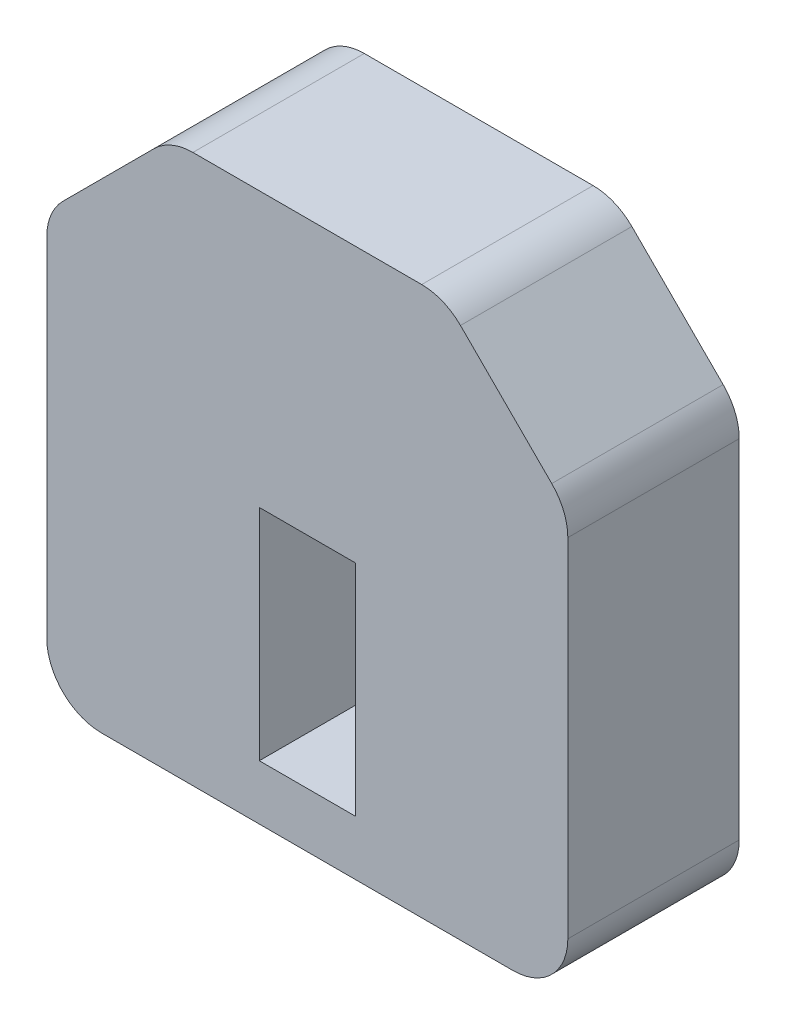
SolidWorks part; units mm, degrees
ref_plane "Front Plane" through (0, 0, 0) normal (0, 0, 1) x (1, 0, 0)
ref_plane "Top Plane" through (0, 0, 0) normal (0, 1, 0) x (1, 0, 0)
ref_plane "Right Plane" through (0, 0, 0) normal (1, 0, 0) x (0, 0, -1)
sketch "Sketch1" plane through (0, 0, 0) normal (0, 0, 1) x (1, 0, 0)
  line L1 (19, -20) -> (-19, -20)
  line L2 (19, -20) -> (19, 20)
  line L3 (19, 20) -> (-19, 20)
  line L4 (-19, -20) -> (-19, 20)
  line L5 (19, -20) -> (-19, 20) construction
  line L6 (19, 20) -> (-19, -20) construction
  point P0 (0, 0)
  dimension "D1" = 38
  dimension "D2" = 40
extrude "Boss-Extrude1" add sketch "Sketch1" along normal blind 12.5
sketch "Sketch2" plane through (0, 0, 12.5) normal (0, 0, 1) x (1, 0, 0)
  line L0 (0, -1000) -> (0, 49000) construction
  line L1 (-19, -20) -> (19, -20) construction
  line L2 (3.5, 0) -> (-3.5, 0)
  line L3 (3.5, 0) -> (3.5, -20)
  line L4 (3.5, -20) -> (-3.5, -20)
  line L5 (-3.5, 0) -> (-3.5, -20)
  line L6 (3.5, 0) -> (-3.5, -20) construction
  line L7 (3.5, -20) -> (-3.5, 0) construction
  line L9 (3.5, -16) -> (-3.5, -16)
  line L10 (3.5, -16) -> (3.5, -20)
  line L11 (3.5, -20) -> (-3.5, -20)
  line L12 (-3.5, -16) -> (-3.5, -20)
  line L13 (3.5, -16) -> (-3.5, -20) construction
  line L14 (3.5, -20) -> (-3.5, -16) construction
  point P1 (0, -10)
  point P10 (0, -18)
  dimension "D1" = 7
  dimension "D2" = 4
  dimension "D3" = 16
extrude "Cut-Extrude1" cut sketch "Sketch2" against normal blind 12 contours L9 L3 L2 L5
chamfer "Chamfer1" distance 9 angle 45 2 edges at (19, 20, 6.25) (-19, 20, 6.25)
fillet "Fillet1" radius 4 6 edges at (-19, -20, 6.25) (19, -20, 6.25) (19, 11, 6.25) (10, 20, 6.25) (-10, 20, 6.25) (-19, 11, 6.25)
